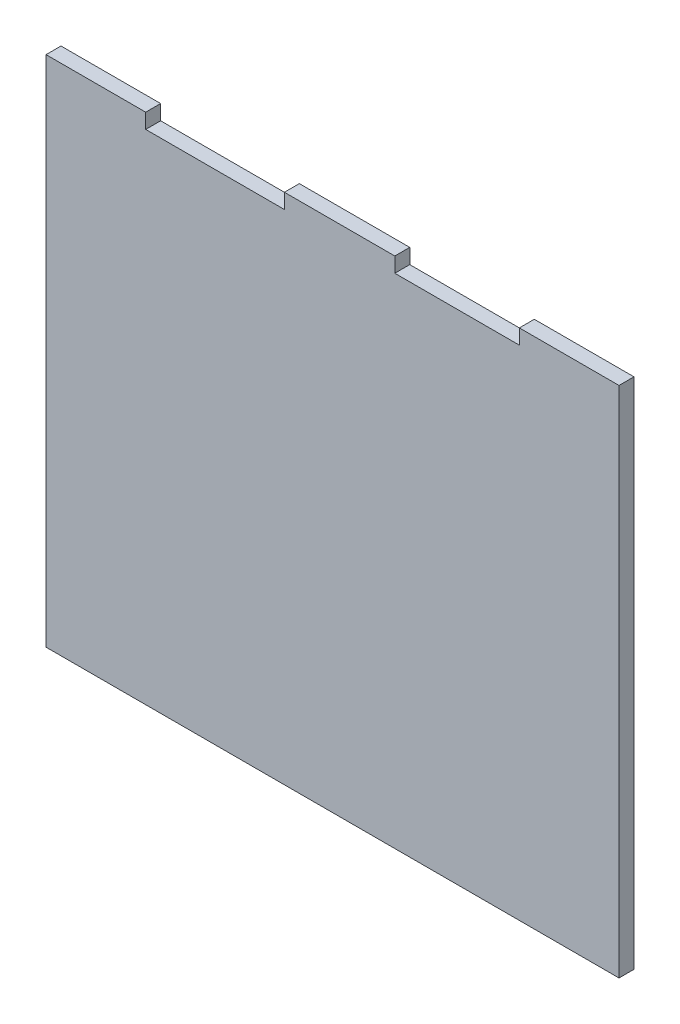
SolidWorks part; units mm, degrees
ref_plane "Front Plane" through (0, 0, 0) normal (0, 0, 1) x (1, 0, 0)
ref_plane "Top Plane" through (0, 0, 0) normal (0, 1, 0) x (1, 0, 0)
ref_plane "Right Plane" through (0, 0, 0) normal (1, 0, 0) x (0, 0, -1)
sketch "Sketch1" plane through (0, 0, 0) normal (0, 0, 1) x (1, 0, 0)
  line L1 (-56.5, 50) -> (58.5, 50)
  line L2 (-56.5, 50) -> (-56.5, -50)
  line L3 (-56.5, -50) -> (58.5, -50)
  line L4 (58.5, 50) -> (58.5, -50)
  line L5 (58.5, 50) -> (38.5, 50)
  line L6 (58.5, 50) -> (58.5, 53)
  line L7 (58.5, 53) -> (38.5, 53)
  line L8 (38.5, 50) -> (38.5, 53)
  line L9 (-56.5, 50) -> (-36.5, 50)
  line L10 (-56.5, 50) -> (-56.5, 53)
  line L11 (-56.5, 53) -> (-36.5, 53)
  line L12 (-36.5, 50) -> (-36.5, 53)
  line L13 (-8.66, 50) -> (13.5, 50)
  line L14 (-8.66, 50) -> (-8.66, 53)
  line L15 (-8.66, 53) -> (13.5, 53)
  line L16 (13.5, 50) -> (13.5, 53)
  dimension "D1" = 115
  dimension "D2" = 100
  dimension "D3" = 50
  dimension "D4" = 56.5
  dimension "D5" = 3
  dimension "D6" = 3
  dimension "D7" = 20
  dimension "D8" = 20
  dimension "D9" = 22.16
  dimension "D10" = 25
  dimension "D11" = 3
extrude "Boss-Extrude1" add sketch "Sketch1" along normal blind 3 contours L4 L1 L2 L3 | L1 L16 L15 L14 | L8 L1 L6 L7 | L10 L11 L12 L9
